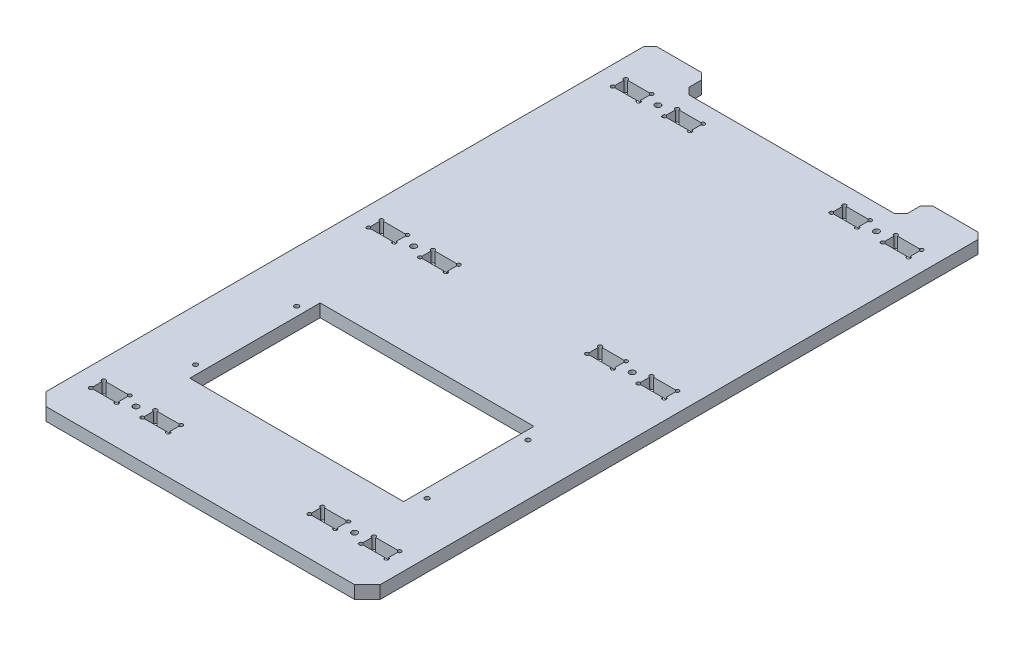
SolidWorks part; units mm, degrees
material "POLICARB. TRANSP."
ref_plane "Front Plane" through (0, 0, 0) normal (0, 0, 1) x (1, 0, 0)
ref_plane "Top Plane" through (0, 0, 0) normal (0, 1, 0) x (1, 0, 0)
ref_plane "Right Plane" through (0, 0, 0) normal (1, 0, 0) x (0, 0, -1)
sketch "Sketch1" plane through (0, 0, 0) normal (0, 1, 0) x (1, 0, 0)
  line L1 (130, 220) -> (-130, 220)
  line L2 (130, 220) -> (130, -220)
  line L3 (130, -220) -> (-130, -220)
  line L4 (-130, 220) -> (-130, -220)
  line L5 (0, -220) -> (0, 220) construction
  line L6 (130, 0) -> (-130, 0) construction
  point P0 (0, 0)
  dimension "D1" = 260
  dimension "D2" = 440
extrude "Extrude1" add sketch "Sketch1" along normal blind 10
sketch "Sketch2" plane through (0, 10, 0) normal (0, 1, 0) x (1, 0, 0)
  line L0 (-130, -220) -> (130, -220) construction
  line L1 (-120, -220) -> (120, -220)
  line L2 (-120, -220) -> (-120, -240)
  line L3 (-120, -240) -> (120, -240)
  line L4 (120, -220) -> (120, -240)
  line L5 (0, 0) -> (0, -220) construction
  line L6 (-130, 220) -> (-130, -220) construction
  dimension "D1" = 20
  dimension "D2" = 10
extrude "Extrude2" [suppressed] add sketch "Sketch2" against normal blind 10
sketch "Sketch3" plane through (0, 10, 0) normal (0, 1, 0) x (1, 0, 0)
  line L0 (130, 220) -> (-130, 220) construction
  line L1 (-130, 220) -> (130, 220)
  line L2 (-130, 220) -> (-130, 260)
  line L3 (-130, 260) -> (130, 260)
  line L4 (130, 220) -> (130, 260)
  line L5 (0, 0) -> (0, 220) construction
  line L7 (130, -220) -> (130, 220) construction
  dimension "D1" = 40
extrude "Extrude3" add sketch "Sketch3" against normal blind 10
extrude "Cut-Extrude1" cut sketch "Sketch4" against normal up to surface (10 mm away) up to face at (0, 10, -20)
sketch "Sketch4" plane through (130, 0, -206) normal (0, -1, 0) x (1, 0, 0)
  line L0 (-260, -54) -> (-260, 426) construction
  line L1 (-245, 396) -> (-225, 396)
  line L2 (-245, 396) -> (-245, 386)
  line L3 (-245, 386) -> (-225, 386)
  line L4 (-225, 396) -> (-225, 386)
  line L5 (-205, 396) -> (-185, 396)
  line L6 (-205, 396) -> (-205, 386)
  line L7 (-205, 386) -> (-185, 386)
  line L8 (-185, 396) -> (-185, 386)
  line L9 (-75, 396) -> (-55, 396)
  line L10 (-75, 396) -> (-75, 386)
  line L11 (-75, 386) -> (-55, 386)
  line L12 (-55, 396) -> (-55, 386)
  line L13 (-35, 396) -> (-15, 396)
  line L14 (-35, 396) -> (-35, 386)
  line L15 (-35, 386) -> (-15, 386)
  line L16 (-15, 396) -> (-15, 386)
  line L17 (-245, 180) -> (-225, 180)
  line L18 (-245, 180) -> (-245, 170)
  line L19 (-245, 170) -> (-225, 170)
  line L20 (-225, 180) -> (-225, 170)
  line L21 (-260, 426) -> (0, 426) construction
  line L22 (-205, 180) -> (-185, 180)
  line L23 (-205, 180) -> (-205, 170)
  line L24 (-205, 170) -> (-185, 170)
  line L25 (-185, 180) -> (-185, 170)
  line L26 (-75, 180) -> (-55, 180)
  line L27 (-75, 180) -> (-75, 170)
  line L28 (-75, 170) -> (-55, 170)
  line L29 (-55, 180) -> (-55, 170)
  line L30 (-35, 180) -> (-15, 180)
  line L31 (-35, 180) -> (-35, 170)
  line L32 (-35, 170) -> (-15, 170)
  line L33 (-15, 180) -> (-15, 170)
  line L35 (-245, -10) -> (-225, -10)
  line L36 (-245, -10) -> (-245, -20)
  line L37 (-245, -20) -> (-225, -20)
  line L38 (-225, -10) -> (-225, -20)
  line L39 (-205, -10) -> (-185, -10)
  line L40 (-205, -10) -> (-205, -20)
  line L41 (-205, -20) -> (-185, -20)
  line L42 (-185, -10) -> (-185, -20)
  line L44 (-75, -10) -> (-55, -10)
  line L45 (-75, -10) -> (-75, -20)
  line L46 (-75, -20) -> (-55, -20)
  line L47 (-55, -10) -> (-55, -20)
  line L48 (-35, -10) -> (-15, -10)
  line L49 (-35, -10) -> (-35, -20)
  line L50 (-35, -20) -> (-15, -20)
  line L51 (-15, -10) -> (-15, -20)
  dimension "D1" = 20
  dimension "D2" = 10
  dimension "D3" = 15
  dimension "D4" = 30
  dimension "D5" = 216
  dimension "D6" = 190
  dimension "D7" = 20
  dimension "D8" = 110
  dimension "D9" = 20
  dimension "D10" = 10
  dimension "D11" = 15
  dimension "D12" = 20
  dimension "D13" = 110
  dimension "D14" = 20
  dimension "D15" = 20
  dimension "D16" = 10
  dimension "D17" = 20
  dimension "D18" = 20
  dimension "D19" = 15
  dimension "D20" = 110
  dimension "D21" = 20
sketch "Sketch5" plane through (0, 0, 0) normal (0, -1, 0) x (-1, 0, 0)
  line L0 (96.5, -190) -> (95, -190)
  line L1 (115, -190) -> (113.5, -190)
  line L2 (115, -190) -> (115, -188.5)
  line L3 (115, -180) -> (113.5, -180)
  line L4 (95, -190) -> (95, -188.5)
  line L5 (115, -181.5) -> (115, -180)
  line L6 (96.5, -180) -> (95, -180)
  line L7 (95, -181.5) -> (95, -180)
  arc A0 (113.5, -190) -> (115, -188.5) centre (115, -190) ccw
  arc A1 (115, -181.5) -> (113.5, -180) centre (115, -180) ccw
  arc A2 (96.5, -180) -> (95, -181.5) centre (95, -180) ccw
  arc A3 (95, -188.5) -> (96.5, -190) centre (95, -190) ccw
  dimension "D1" = 3
extrude "Extrude4" cut sketch "Sketch5" against normal blind 10
ref_plane "Plane1" through (-85, 0, 0) normal (1, 0, 0) x (0, 0, -1)
mirror "Mirror1" about plane through (-85, 0, 0) normal (1, 0, 0) of "Extrude4"
ref_plane "Plane2" through (0, 0, 0) normal (1, 0, 0) x (0, 0, -1)
mirror "Mirror2" about plane through (0, 0, 0) normal (1, 0, 0) of "Mirror1", "Extrude4"
ref_plane "Plane3" through (0, 0, 77) normal (0, 0, -1) x (-1, 0, 0)
mirror "Mirror3" about plane through (0, 0, 77) normal (0, 0, -1) of "Mirror2", "Mirror1", "Extrude4"
ref_plane "Plane4" through (0, 0, -18) normal (0, 0, 1) x (1, 0, 0)
mirror "Mirror4" about plane through (0, 0, -18) normal (0, 0, 1) of "Mirror2", "Extrude4", "Mirror1"
hole_wizard "M4 Clearance Hole1" positions "Sketch6" profile "Sketch7" hole size "M4" standard "DIN" end condition through all
sketch "Sketch6" plane through (0, 10, 0) normal (0, 1, 0) x (1, 0, 0)
  line L4 (-95, 221) -> (-75, 221) construction
  line L5 (-95, 217.5) -> (-95, 224.5) construction
  line L6 (-75, 224.5) -> (-75, 217.5) construction
  line L8 (75, 217.5) -> (75, 224.5) construction
  line L9 (75, 221) -> (95, 221) construction
  line L10 (95, 224.5) -> (95, 217.5) construction
  line L14 (-95, 27.5) -> (-95, 34.5) construction
  line L15 (-95, 31) -> (-75, 31) construction
  line L16 (-75, 34.5) -> (-75, 27.5) construction
  line L18 (-95, -185) -> (-75, -185) construction
  line L19 (-95, -188.5) -> (-95, -181.5) construction
  line L20 (-75, -181.5) -> (-75, -188.5) construction
  point P0 (-85, 221)
  point P2 (85, 221)
  point P4 (85, 31)
  point P6 (-85, 31)
  point P8 (-85, -185)
  point P10 (85, -185)
sketch "Sketch7" plane through (-85, 10, -221) normal (1, 0, 0) x (0, 0, 1)
  line L0 (0, 0) -> (0, 10)
  line L1 (0, 10) -> (2.25, 10)
  line L2 (2.25, 10) -> (2.25, 0)
  line L5 (2.25, 0) -> (0, 0)
  line L11 (0, -6.35) -> (0, 107.95) construction
  dimension "Thru Hole Dia." = 4.5
  dimension "Thru Hole Depth" = 10
extrude "Cut-Extrude2" cut sketch "Sketch8" against normal up to surface (10 mm away) up to face at (-85, 10, -218.75)
sketch "Sketch8" plane through (130, 0, -206) normal (0, -1, 0) x (1, 0, 0)
  line L0 (-130, 426) -> (-130, -54) construction
  line L1 (-213.15, 351) -> (-46.85, 351)
  line L2 (-213.15, 351) -> (-213.15, 249.6)
  line L3 (-213.15, 249.6) -> (-46.85, 249.6)
  line L4 (-46.85, 351) -> (-46.85, 249.6)
  line L5 (-260, 426) -> (0, 426) construction
  line L6 (0, -54) -> (-260, -54) construction
  dimension "D1" = 166.3
  dimension "D2" = 75
  dimension "D3" = 101.4
extrude "Cut-Extrude3" cut sketch "Sketch9" against normal up to surface (10 mm away) up to face at (0, 0, 94.3)
sketch "Sketch9" plane through (-103.5, 10, 155.65) normal (0, 1, 0) x (-1, 0, 0)
  circle A0 centre (-13.45, -22.05) radius 1.75
  circle A1 centre (-193.55, -22.05) radius 1.75
  circle A3 centre (-13.45, -100.65) radius 1.75
  circle A4 centre (-193.55, -100.55) radius 1.75
chamfer "Chamfer1" distance 10 angle 45 2 edges at (-130, 5, 220) (130, 5, 220)
sketch "Sketch10" plane through (0, 0, 0) normal (0, -1, 0) x (1, 0, 0)
  line L0 (130, -260) -> (-130, -260) construction
  line L1 (-85, -260) -> (85, -260)
  line L2 (-85, -260) -> (-85, -240)
  line L3 (-85, -240) -> (85, -240)
  line L4 (85, -260) -> (85, -240)
  line L5 (0, 0) -> (0, -260) construction
  line L6 (-130, -260) -> (-130, 210) construction
  dimension "D1" = 45
  dimension "D2" = 20
extrude "Extrude6" cut sketch "Sketch10" against normal blind 10
chamfer "Chamfer2" distance 5 angle 45 6 edges at (-130, 5, -260) (-85, 5, -260) (-85, 5, -240) (85, 5, -240) (85, 5, -260) (130, 5, -260)
